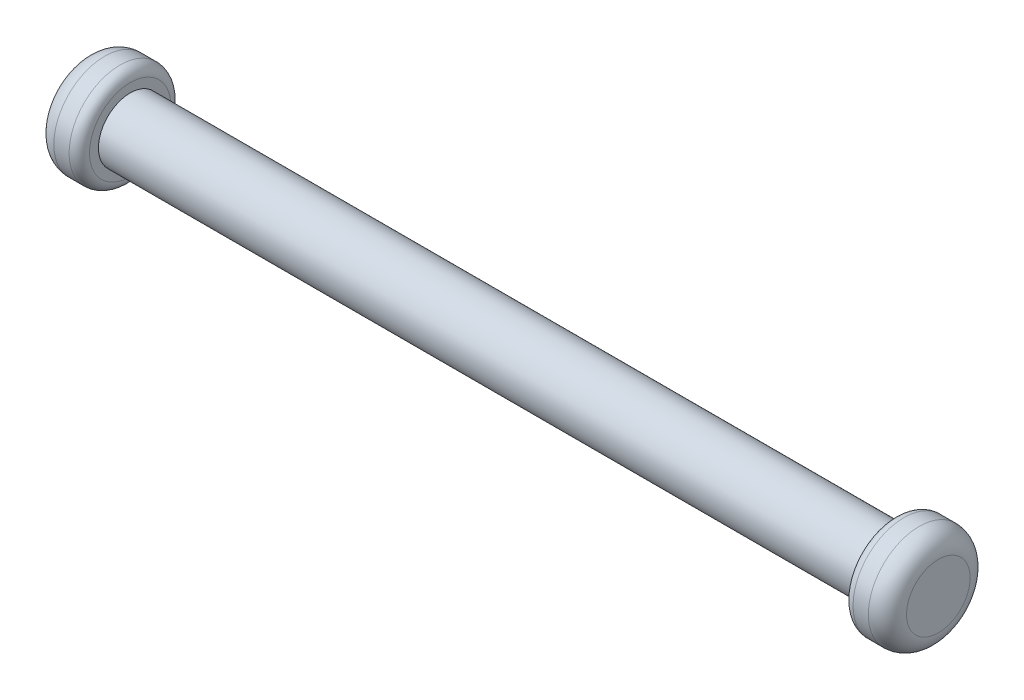
SolidWorks part; units mm, degrees
material "Ст3пс ГОСТ 380-94"
ref_plane "Front Plane" through (0, 0, 0) normal (0, 0, 1) x (1, 0, 0)
ref_plane "Top Plane" through (0, 0, 0) normal (0, 1, 0) x (1, 0, 0)
ref_plane "Right Plane" through (0, 0, 0) normal (1, 0, 0) x (0, 0, -1)
sketch "Эскиз1" plane through (0, 0, 0) normal (0, 0, 1) x (1, 0, 0)
  line L0 (0, 0) -> (0, 4)
  line L1 (0, 4) -> (3.5, 4)
  line L2 (3.5, 4) -> (3.5, 2.5)
  line L3 (3.5, 2.5) -> (63.5, 2.5)
  line L4 (63.5, 2.5) -> (63.5, 4)
  line L5 (63.5, 4) -> (67, 4)
  line L6 (67, 4) -> (67, 0)
  line L7 (67, 0) -> (0, 0)
  line L8 (0, 0) -> (-3.168, 0) construction
  dimension "D1" = 5
  dimension "D2" = 8
  dimension "D3" = 8
  dimension "D4" = 3.5
  dimension "D5" = 3.5
  dimension "D6" = 60
revolve "Повернуть1" add sketch "Эскиз1" angle 360 about L8
fillet "Скругление1" radius 0.8 2 edges at (63.5, 0, -4) (3.5, 0, -4)
fillet "Скругление2" radius 1.5 2 edges at (67, 0, -4) (0, 0, -4)
